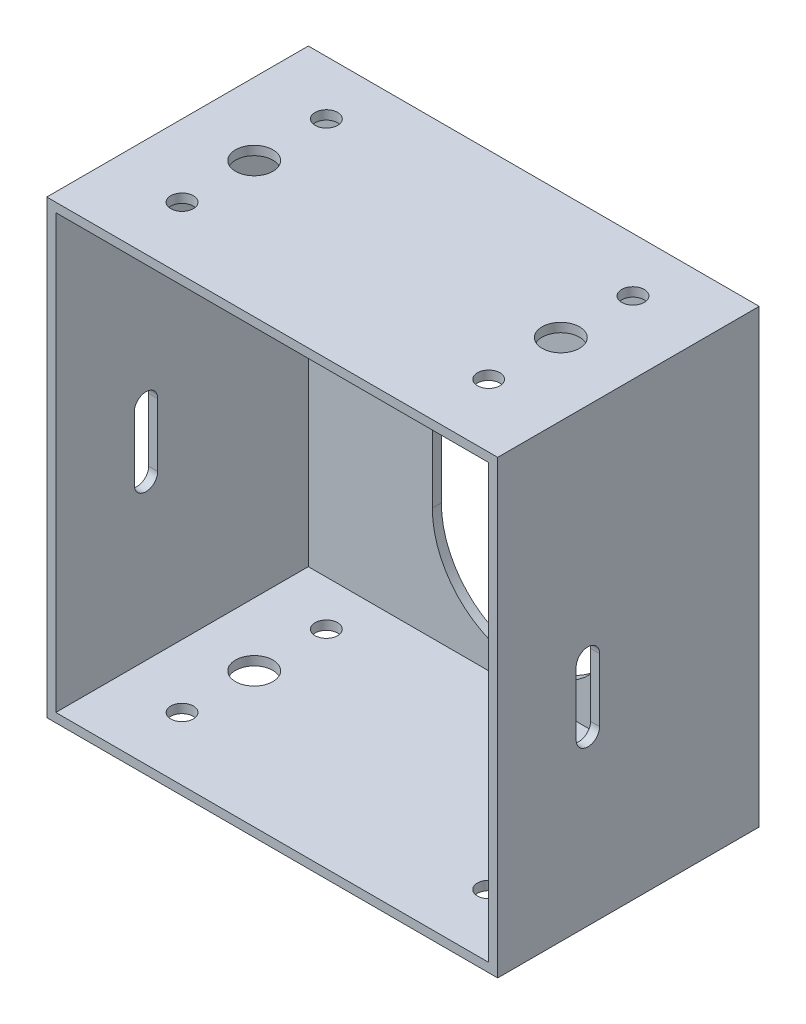
SolidWorks part; units mm, degrees
material "1.0503 (C45)"
ref_plane "Front Plane" through (0, 0, 0) normal (0, 0, 1) x (1, 0, 0)
ref_plane "Top Plane" through (0, 0, 0) normal (0, 1, 0) x (1, 0, 0)
ref_plane "Right Plane" through (0, 0, 0) normal (1, 0, 0) x (0, 0, -1)
sketch "Sketch1" plane through (0, 0, 0) normal (0, 0, 1) x (1, 0, 0)
  line L1 (50, 50) -> (-50, 50)
  line L2 (50, 50) -> (50, -50)
  line L3 (50, -50) -> (-50, -50)
  line L4 (-50, 50) -> (-50, -50)
  line L5 (0, -50) -> (0, 50) construction
  line L6 (50, 0) -> (-50, 0) construction
  point P0 (0, 0)
  dimension "D1" = 100
extrude "Extrude-Thin1" add sketch "Sketch1" along normal mid plane 58 thin thin type one direction reverse wall 2
sketch "Sketch2" plane through (0, 0, -29) normal (0, 0, -1) x (-1, 0, 0)
  line L4 (50, -50) -> (50, 50)
  line L5 (50, 50) -> (-50, 50)
  line L6 (-50, 50) -> (-50, -50)
  line L7 (-50, -50) -> (50, -50)
  line L8 (50, -50) -> (50, 50)
  line L9 (50, 50) -> (-50, 50)
  line L10 (-50, 50) -> (-50, -50)
  line L11 (-50, -50) -> (50, -50)
  dimension "D1" = 0
extrude "Boss-Extrude1" add sketch "Sketch2" against normal blind 2
sketch "Sketch3" plane through (0, 0, -27) normal (0, 0, 1) x (1, 0, 0)
  line L0 (0, -23) -> (0, 25) construction
  line L1 (-20.5, -23) -> (-20.5, 10)
  line L2 (20.5, -23) -> (20.5, 10)
  line L3 (-20.5, 10) -> (20.5, 10)
  line L4 (50, 50) -> (-50, 50) construction
  arc A0 (-20.5, -23) -> (20.5, -23) centre (0, -23) ccw
  point P4 (0, 0)
  dimension "D1" = 41
  dimension "D2" = 40
  dimension "D3" = 10
  dimension "D4" = 33
extrude "Cut-Extrude1" cut sketch "Sketch3" against normal up to next
sketch "Sketch4" plane through (-50, 0, 0) normal (-1, 0, 0) x (0, 0, 1)
  line L0 (9, 1) -> (9, -13) construction
  line L2 (11.6, 1) -> (11.6, -13)
  line L3 (6.4, 1) -> (6.4, -13)
  line L4 (-29, 50) -> (-29, -50) construction
  line L6 (29, 50) -> (-29, 50) construction
  arc A0 (11.6, 1) -> (6.4, 1) centre (9, 1) ccw
  arc A1 (6.4, -13) -> (11.6, -13) centre (9, -13) ccw
  point P4 (9, -6)
  dimension "D4" = 46.4
  dimension "D1" = 5.2
  dimension "D2" = 14
  dimension "D3" = 38
  dimension "D5" = 1
  dimension "D6" = 38
extrude "Cut-Extrude2" cut sketch "Sketch4" against normal blind 160
sketch "Sketch6" plane through (0, 0, -29) normal (0, 0, -1) x (-1, 0, 0)
  line L0 (0, 10) -> (0, 30) construction
  line L1 (20.5, 10) -> (-20.5, 10) construction
  line L2 (-2.6, 10) -> (-2.6, 30)
  line L3 (2.6, 10) -> (2.6, 30)
  line L4 (49, 30) -> (0, 30) construction
  arc A0 (-2.6, 10) -> (2.6, 10) centre (0, 10) ccw
  arc A1 (2.6, 30) -> (-2.6, 30) centre (0, 30) ccw
  point P5 (0, 20)
  dimension "D1" = 5.2
  dimension "D2" = 20
extrude "Cut-Extrude3" cut sketch "Sketch6" against normal blind 160
chamfer "Chamfer1" distance 1 angle 45 2 edges at (-2.6, 10, -28) (2.6, 10, -28)
sketch "Sketch7" plane through (0, 50, 0) normal (0, 1, 0) x (1, 0, 0)
  line L0 (50, -29) -> (-50, -29) construction
  circle A0 centre (-34, 1) radius 4.15
  circle A1 centre (34, 1) radius 4.15
  dimension "D1" = 34
  dimension "D2" = 8.3
  dimension "D3" = 8.3
  dimension "D4" = 34
  dimension "D5" = 68
  dimension "D6" = 30
extrude "Cut-Extrude4" cut sketch "Sketch7" against normal through all both and the other way through all
sketch "Sketch8" plane through (0, 50, 0) normal (0, 1, 0) x (1, 0, 0)
  line L0 (50, -29) -> (-50, -29) construction
  line L1 (-50, -29) -> (-50, 29) construction
  line L2 (50, -29) -> (50, 29) construction
  circle A0 centre (-34, 17) radius 2.5
  circle A1 centre (-34, -15) radius 2.5
  circle A2 centre (34, 17) radius 2.5
  circle A3 centre (34, -15) radius 2.5
  point P16 (0, 0)
  point P17 (0, 0)
  point P18 (0, 0)
  point P21 (0, 0)
  dimension "D1" = 5
  dimension "D2" = 5
  dimension "D3" = 5
  dimension "D4" = 32
  dimension "D5" = 14
  dimension "D6" = 16
  dimension "D7" = 16
extrude "Cut-Extrude5" cut sketch "Sketch8" against normal blind 177
